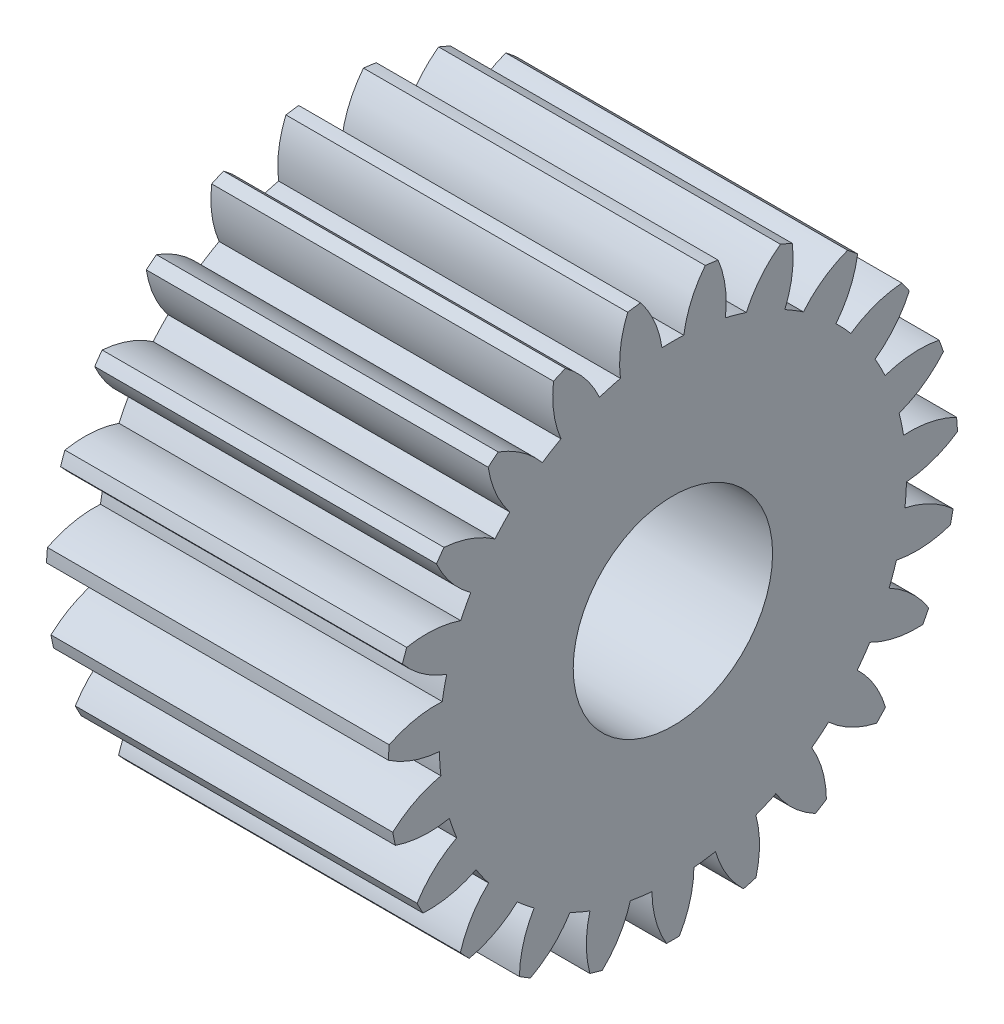
SolidWorks part; units mm, degrees
ref_plane "Plane1" through (0, 0, 0) normal (0, 0, 1) x (1, 0, 0)
ref_plane "Plane2" through (0, 0, 0) normal (0, 1, 0) x (1, 0, 0)
ref_plane "Plane3" through (0, 0, 0) normal (1, 0, 0) x (0, 0, -1)
sketch "HoldingSke" plane through (0, 0, 0) normal (0, 1, 0) x (1, 0, 0)
  line L0 (0, 0) -> (0.2301, -0.0977)
  line L1 (-15, 0) -> (100, 0) construction
  line L2 (0, 0) -> (-2.1039, 2.3779)
  line L3 (0, 0) -> (-11.863, 4.5341)
  line L4 (0, 0) -> (7.9495, 3.3744)
  line L5 (0, 0) -> (-46.8476, -17.4728)
  line L6 (0, 0) -> (-49.7378, -33.5582)
  line L7 (-2.1039, 2.3779) -> (10.8111, 60.9715)
  line L8 (-76.2, 54.61) -> (-72.9, 54.61)
  line L9 (-71.009, 38.7566) -> (-53.1078, 45.2721)
  line L10 (-76.2, 71.12) -> (104.1128, 71.12)
  line L11 (0, 0) -> (-60, 0)
  line L12 (-76.2, 101.6) -> (-76.073, 101.6)
  line L13 (24.9733, 27.94) -> (52.9518, 28.4284)
  line L14 (24.9733, 27.94) -> (24.9743, 27.94)
  line L15 (24.9733, 27.94) -> (100.4006, 29.5858)
  line L16 (-63.627, -4) -> (-12.827, -4)
  circle A0 centre (0, 0) radius 17.5
  circle A1 centre (0, 0) radius 37.5
  circle A2 centre (0, 0) radius 37.5
  circle A3 centre (0, 0) radius 17.5
  dimension "MHD" = 75
  dimension "Hub_dia" = 75
  dimension "Bore" = 35
  dimension "MBD" = 35
  dimension "Num_teeth" = 23
  dimension "Pitch" = 0.25
  dimension "Overall_len" = 50
  dimension "Show_teeth" = 23
  dimension "Thickness" = 60
  dimension "OAL" = 60.0001
  dimension "T_dim" = 3.3
  dimension "Ap" = 20
  dimension "H" = 19.05
  dimension "Pitch_radius" = 180.3128
  dimension "Width" = 60
  dimension "Backlash" = 0.127
  dimension "Addendum_fac" = 1
  dimension "Dedendum_fac" = 1.25
  dimension "Clearance_fac" = 0.25
  dimension "Dedendum_add" = 0.001
  dimension "Module" = 4
sketch "BasProSke" plane through (0, 0, 0) normal (0, 1, 0) x (1, 0, 0)
  line L0 (-10, 0) -> (60, 0) construction
  line L1 (0, 0) -> (0, 50)
  line L2 (0, 0) -> (60, 0)
  line L3 (60, 0) -> (60, 50)
  line L4 (60, 50) -> (0, 50)
  dimension "Thickness" = 60
  dimension "Diameter" = 100
revolve "Base-Revolve" add sketch "BasProSke" angle 360 about L0
sketch "TooCutSke" plane through (0, 0, 0) normal (1, 0, 0) x (0, 0, -1)
  line L1 (0, 0) -> (0, 107) construction
  line L2 (0, 0) -> (-3.3613, 45.877) construction
  line L3 (0, 0) -> (-12.5021, 90.9597) construction
  line L4 (-3.3613, 45.877) -> (-6.2511, 45.4798) construction
  arc A0 (1.9097, 40.9545) -> (-1.9097, 40.9545) centre (0, 0) ccw
  arc A1 (5.6984, 49.6998) -> (-5.6984, 49.6998) centre (0, 0) ccw
  circle A2 centre (0, 0) radius 46 construction
  circle A3 centre (0, 0) radius 43.2259 construction
  arc A4 (-1.9097, 40.9545) -> (-5.6984, 49.6998) centre (-20.1117, 38.2622) ccw
  arc A5 (5.6984, 49.6998) -> (1.9097, 40.9545) centre (20.1117, 38.2622) ccw
  dimension "Root_dia" = 81.998
  dimension "Overcut_dia" = 100.0508
  dimension "Pitch_dia" = 92
  dimension "Base_dia" = 86.4517
  dimension "Flank_rad" = 18.4
  dimension "Half_ang" = 7.826
  dimension "Half_CT" = 2.9169
extrude "ToothCut" cut sketch "TooCutSke" along normal through all
fillet "Breaks" [suppressed] radius 0.08
fillet "RootFillets" [suppressed] radius 1.001
pattern_circular "TeethCuts" count 23 every 15.652 about axis through (-10, 0, 0) along (1, 0, 0) of "ToothCut", "RootFillets", "Breaks"
sketch "HubNeaOneSke" plane through (0, 0, 0) normal (-1, 0, 0) x (0, 0, 1)
  circle A0 centre (0, 0) radius 37.5
  dimension "Diameter" = 75
extrude "HubNearOne" [suppressed] add sketch "HubNeaOneSke" along normal blind 38.0001
sketch "HubNeaBotSke" plane through (0, 0, 0) normal (-1, 0, 0) x (0, 0, 1)
  circle A0 centre (0, 0) radius 37.5
  dimension "Diameter" = 75
extrude "HubNearBoth" [suppressed] add sketch "HubNeaBotSke" along normal blind 19
ref_plane "FarPln" through (60, 0, 0) normal (1, 0, 0) x (0, 0, -1)
sketch "HubFarSke" plane through (60, 0, 0) normal (1, 0, 0) x (0, 0, -1)
  circle A0 centre (0, 0) radius 37.5
  dimension "Diameter" = 75
extrude "HubFar" [suppressed] add sketch "HubFarSke" along normal blind 19
sketch "BorSke" plane through (0, 0, 0) normal (1, 0, 0) x (0, 0, -1)
  circle A0 centre (0, 0) radius 17.5
  dimension "Diameter" = 35
extrude "Bore" cut sketch "BorSke" along normal mid plane 120.0001
sketch "KeySke" plane through (0, 0, 0) normal (1, 0, 0) x (0, 0, -1)
  line L0 (-5, 0) -> (-5, 20.8)
  line L1 (-5, 20.8) -> (5, 20.8)
  line L2 (5, 20.8) -> (5, 0)
  line L3 (0, 0) -> (0, 34) construction
  line L4 (-5, 0) -> (5, 0)
  dimension "Offset" = 20.8
  dimension "Width" = 10
extrude "Keyway" [suppressed] cut sketch "KeySke" along normal mid plane 120.0001
pattern_circular "Keyway2" [suppressed] count 2 every 90 about axis through (-10, 0, 0) along (1, 0, 0)
equation "' \"Module@HoldingSke\" = 6.35"
equation "' \"Num_teeth@HoldingSke\" = 12"
equation "' \"Ap@HoldingSke\" =  20"
equation "' \"Ap@HoldingSke\" = 20"
equation "' \"Width@HoldingSke\" = 0.5 * 25.4"
equation "' \"Hub_dia@HoldingSke\"= 1 * 25.4"
equation "' \"Hub_dia@HoldingSke\" = 1 * 25.4"
equation "' \"Overall_len@HoldingSke\" = 1.0 * 25.4"
equation "' \"Bore@HoldingSke\" = 0.75 * 25.4"
equation "' \"T_dim@HoldingSke\" = 0.1 * 25.4"
equation "' \"Width@KeySke\" = 0.25 * 25.4"
equation "' \"Show_teeth@HoldingSke\" = 13"
equation "' \"Backlash@HoldingSke\" = 0.009 * 25.4"
equation "' \"Addendum_fac@HoldingSke\" = 1.0"
equation "' \"Dedendum_fac@HoldingSke\" = 1.25"
equation "' \"Dedendum_add@HoldingSke\" = 0.00005 * 25.4"
equation "' \"Clearance_fac@HoldingSke\" = 0.25"
equation "\"Pitch@HoldingSke\" = 1 / \"Module@HoldingSke\""
equation "\"Overcut_dia@TooCutSke\" = (\"Num_teeth@HoldingSke\" + 2 * \"Addendum_fac@HoldingSke\") / \"Pitch@HoldingSke\" + 0.002 * 25.4"
equation "\"Pitch_dia@TooCutSke\" = \"Num_teeth@HoldingSke\" / \"Pitch@HoldingSke\""
equation "\"Base_dia@TooCutSke\" = \"Num_teeth@HoldingSke\" / \"Pitch@HoldingSke\" * cos((\"Ap@HoldingSke\"  * 3.14159265 / 180))"
equation "\"Root_dia@TooCutSke\" = (\"Num_teeth@HoldingSke\" + 2) / \"Pitch@HoldingSke\" - 2 * (\"Addendum_fac@HoldingSke\" + \"Dedendum_fac@HoldingSke\") / \"Pitch@HoldingSke\" - \"Dedendum_add@HoldingSke\" * 2"
equation "\"Half_ang@TooCutSke\" = 180 / \"Num_teeth@HoldingSke\""
equation "\"Half_CT@TooCutSke\" = \"Num_teeth@HoldingSke\" / \"Pitch@HoldingSke\" * sin((3.14159265 / 2 / \"Num_teeth@HoldingSke\")) / 2 - 7 * \"Backlash@HoldingSke\" / 4"
equation "\"Flank_rad@TooCutSke\" = \"Num_teeth@HoldingSke\" / \"Pitch@HoldingSke\" / 5"
equation "\"Radius@RootFillets\" = \"Clearance_fac@HoldingSke\" / \"Pitch@HoldingSke\" + \"Dedendum_add@HoldingSke\""
equation "\"Break_rad@Breaks\" = 0.02 / \"Pitch@HoldingSke\""
equation "\"Thickness@HoldingSke\" = \"Width@HoldingSke\""
equation "\"OAL@HoldingSke\" = \"Thickness@HoldingSke\""
equation "\"MHD@HoldingSke\" = (\"Num_teeth@HoldingSke\" + 2) / \"Pitch@HoldingSke\" - 2 * (\"Addendum_fac@HoldingSke\" + \"Dedendum_fac@HoldingSke\")  / \"Pitch@HoldingSke\" - \"Dedendum_add@HoldingSke\" * 2"
equation "\"MBD@HoldingSke\" = (\"Num_teeth@HoldingSke\" + 2) / \"Pitch@HoldingSke\" - 2 * (\"Addendum_fac@HoldingSke\" + \"Dedendum_fac@HoldingSke\")  / \"Pitch@HoldingSke\" - \"Dedendum_add@HoldingSke\" * 2 - 0.002 * 25.4"
equation "\"MHD@HoldingSke\" = ((sgn( \"MHD@HoldingSke\" - \"Hub_dia@HoldingSke\" )-1)*( \"MHD@HoldingSke\" - \"Hub_dia@HoldingSke\" ))/-2+ \"Hub_dia@HoldingSke\""
equation "\"MBD@HoldingSke\" = ((sgn( \"MBD@HoldingSke\" - \"Bore@HoldingSke\" )-1)*( \"MBD@HoldingSke\" - \"Bore@HoldingSke\" ))/-2+ \"Bore@HoldingSke\""
equation "\"OAL@HoldingSke\" = ((sgn( \"OAL@HoldingSke\" - \"Overall_len@HoldingSke\" )+1)*( \"OAL@HoldingSke\" - \"Overall_len@HoldingSke\" ))/2 + \"Overall_len@HoldingSke\" + 0.000002 * 25.4"
equation "\"Num_teeth@TeethCuts\" = int( \"Show_teeth@HoldingSke\" ) + 1"
equation "\"Num_teeth@TeethCuts\" = ((sgn( \"Num_teeth@TeethCuts\" - \"Num_teeth@HoldingSke\" )-1)*( \"Num_teeth@TeethCuts\" - \"Num_teeth@HoldingSke\" ))/-2+ \"Num_teeth@HoldingSke\""
equation "\"Num_teeth@TeethCuts\" = ((sgn( \"Num_teeth@TeethCuts\" - 2.0)+1)*( \"Num_teeth@TeethCuts\" - 2.0))/2 +2.0"
equation "\"Angle@TeethCuts\" = 360.0 / \"Num_teeth@HoldingSke\""
equation "\"Diameter@BasProSke\" = (\"Num_teeth@HoldingSke\" + 2 * \"Addendum_fac@HoldingSke\") / \"Pitch@HoldingSke\""
equation "\"Thickness@BasProSke\"  = \"Thickness@HoldingSke\""
equation "' \"Fillet_rad@BasProSke\" =  \"Thickness@HoldingSke\" * 0.05"
equation "' \"Fillet_rad@BasProSke\" = \"Thickness@HoldingSke\" * 0.05"
equation "\"MHD@HoldingSke\" = ((sgn( \"MHD@HoldingSke\" - \"Root_dia@TooCutSke\" )-1)*( \"MHD@HoldingSke\" - \"Root_dia@TooCutSke\" ))/-2+ \"Root_dia@TooCutSke\""
equation "\"Diameter@HubNeaOneSke\" = \"MHD@HoldingSke\""
equation "\"Length@HubNearOne\" = \"OAL@HoldingSke\" - \"Thickness@BasProSke\""
equation "\"Diameter@HubNeaBotSke\" = \"MHD@HoldingSke\""
equation "\"Length@HubNearBoth\" = ( \"OAL@HoldingSke\" - \"Thickness@BasProSke\" ) / 2.0"
equation "\"Thickness@FarPln\" = \"Thickness@BasProSke\""
equation "\"Diameter@HubFarSke\" = \"MHD@HoldingSke\""
equation "\"Length@HubFar\" = ( \"OAL@HoldingSke\" - \"Thickness@BasProSke\" ) / 2.0"
equation "\"Diameter@BorSke\" = \"MBD@HoldingSke\""
equation "\"D1@Bore\" = \"OAL@HoldingSke\" * 2.0"
equation "\"D1@Keyway\" = \"OAL@HoldingSke\" * 2.0"
equation "\"Offset@KeySke\" = \"T_dim@HoldingSke\" + \"MBD@HoldingSke\" / 2.0"
